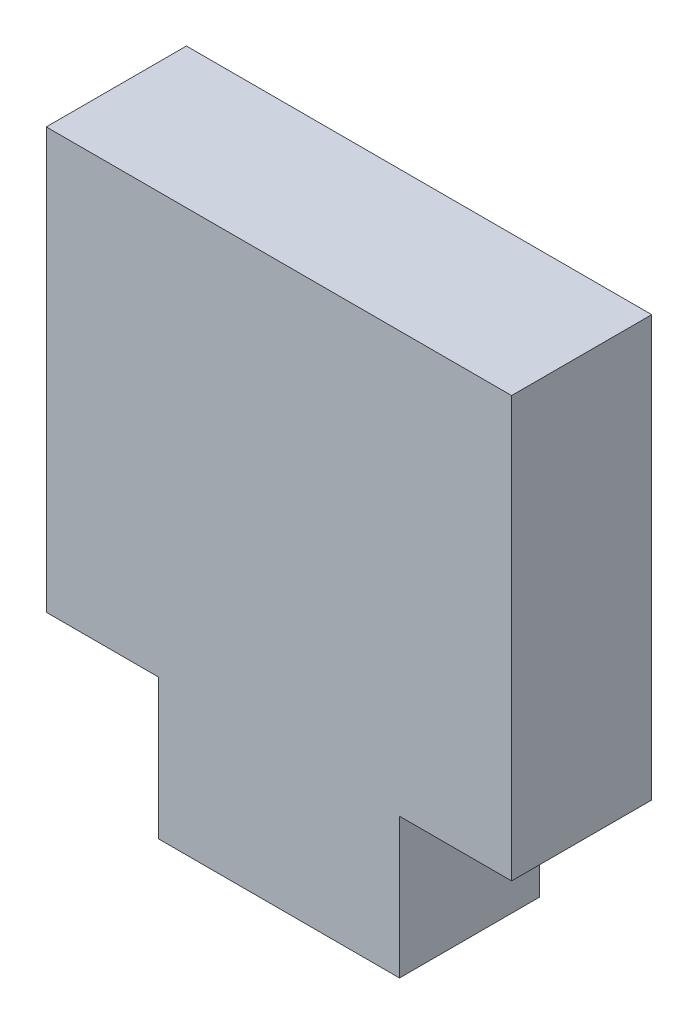
SolidWorks part; units mm, degrees
ref_plane "Front" through (0, 0, 0) normal (0, 0, 1) x (1, 0, 0)
ref_plane "Top" through (0, 0, 0) normal (0, 1, 0) x (1, 0, 0)
ref_plane "Right" through (0, 0, 0) normal (1, 0, 0) x (0, 0, -1)
sketch "Sketch1" plane through (0, 0, 0) normal (0, 0, 1) x (1, 0, 0)
  line L0 (30.6896, 14.3682) -> (22.0853, 14.3682)
  line L1 (30.6896, 14.3682) -> (30.6896, 19.3682)
  line L2 (34.6896, 19.3682) -> (34.6896, 34.3682)
  line L3 (34.6896, 19.3682) -> (30.6896, 19.3682)
  line L4 (22.0853, 14.3682) -> (22.0853, 19.3682)
  line L5 (22.0853, 19.3682) -> (18.0853, 19.3682)
  line L6 (18.0853, 19.3682) -> (18.0853, 34.3682)
  line L7 (34.6896, 34.3682) -> (18.0853, 34.3682)
extrude "Boss-Extrude1" add sketch "Sketch1" along normal blind 5
